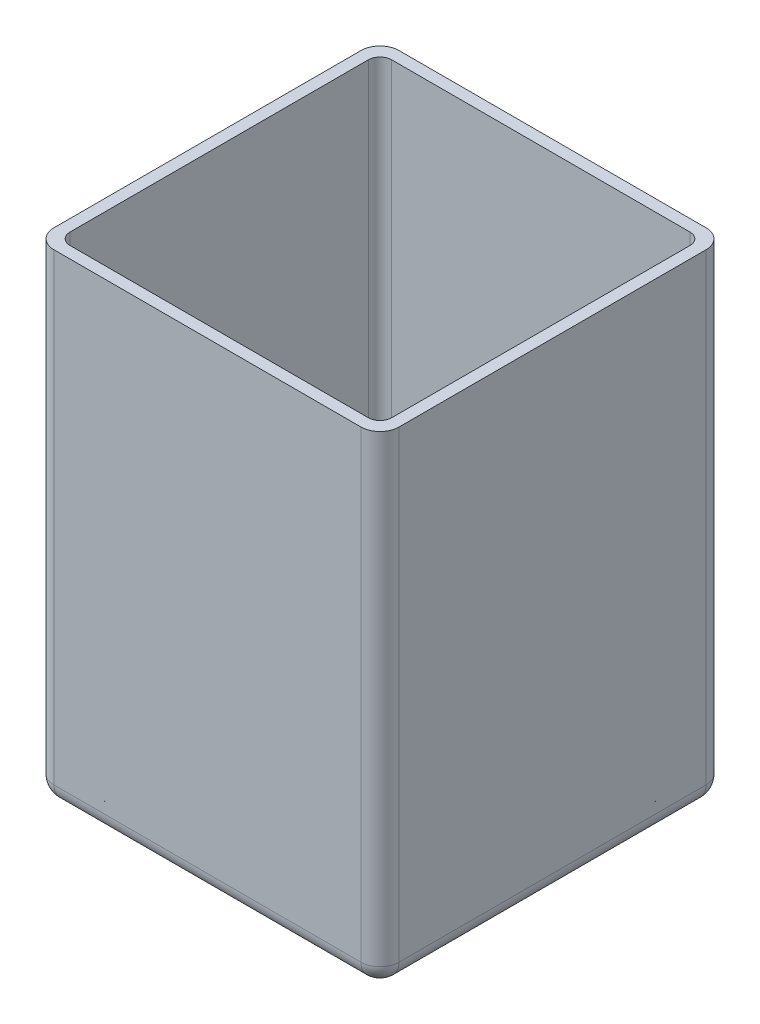
SolidWorks part; units mm, degrees
material "Glass"
ref_plane "Front" through (0, 0, 0) normal (0, 0, 1) x (1, 0, 0)
ref_plane "Top" through (0, 0, 0) normal (0, 1, 0) x (1, 0, 0)
ref_plane "Right" through (0, 0, 0) normal (1, 0, 0) x (0, 0, -1)
sketch "Sketch1" plane through (0, 0, 0) normal (0, 1, 0) x (1, 0, 0)
  line L1 (-59, 59) -> (59, 59)
  line L2 (-59, 59) -> (-59, -59)
  line L3 (-59, -59) -> (59, -59)
  line L4 (59, 59) -> (59, -59)
  line L5 (-59, 59) -> (59, -59) construction
  line L6 (-59, -59) -> (59, 59) construction
  point P0 (0, 0)
  dimension "D1" = 118
extrude "Boss-Extrude1" add sketch "Sketch1" along normal blind 165
shell "Shell1" thickness 4
fillet "Fillet1" radius 4 8 edges at (55, 84.5, 55) (-55, 84.5, 55) (-55, 84.5, -55) (55, 84.5, -55) (0, 4, 55) (-55, 4, 0) (0, 4, -55) (55, 4, 0)
fillet "Fillet2" radius 6.5 8 edges at (0, 0, -59) (-59, 0, 0) (0, 0, 59) (59, 0, 0) (-59, 82.5, -59) (-59, 82.5, 59) (59, 82.5, -59) (59, 82.5, 59)
